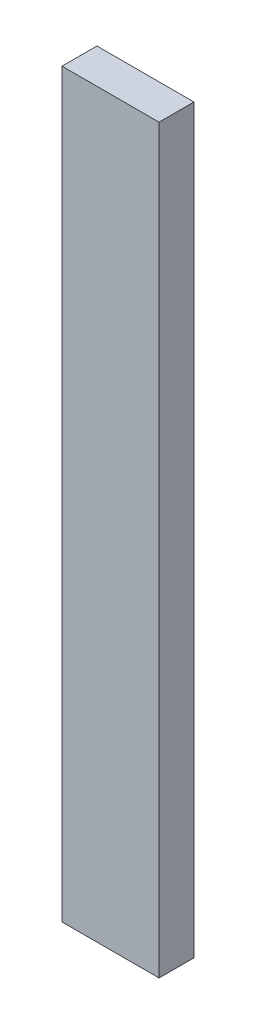
SolidWorks part; units mm, degrees
ref_plane "Front Plane" through (0, 0, 0) normal (0, 0, 1) x (1, 0, 0)
ref_plane "Top Plane" through (0, 0, 0) normal (0, 1, 0) x (1, 0, 0)
ref_plane "Right Plane" through (0, 0, 0) normal (1, 0, 0) x (0, 0, -1)
sketch "Sketch1" plane through (0, 0, 0) normal (0, 0, 1) x (1, 0, 0)
  line L1 (25, 191) -> (-25, 191)
  line L2 (25, 191) -> (25, -191)
  line L3 (25, -191) -> (-25, -191)
  line L4 (-25, 191) -> (-25, -191)
  line L5 (25, 191) -> (-25, -191) construction
  line L6 (25, -191) -> (-25, 191) construction
  point P0 (0, 0)
  dimension "D1" = 382
  dimension "D2" = 50
extrude "Boss-Extrude1" add sketch "Sketch1" along normal blind 18
